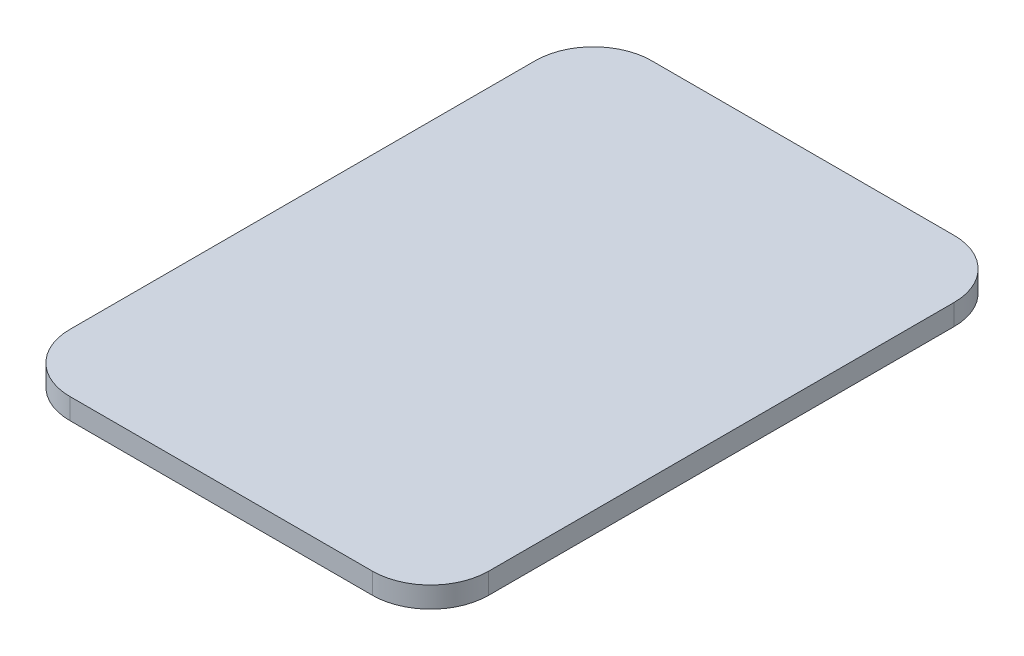
SolidWorks part; units mm, degrees
ref_plane "Front Plane" through (0, 0, 0) normal (0, 0, 1) x (1, 0, 0)
ref_plane "Top Plane" through (0, 0, 0) normal (0, 1, 0) x (1, 0, 0)
ref_plane "Right Plane" through (0, 0, 0) normal (1, 0, 0) x (0, 0, -1)
sketch "Sketch1" plane through (0, 0, 0) normal (0, 1, 0) x (1, 0, 0)
  line L1 (-65, -125) -> (65, -125)
  line L2 (-90, -100) -> (-90, 100)
  line L3 (-65, 125) -> (65, 125)
  line L4 (90, -100) -> (90, 100)
  arc A0 (-90, 100) -> (-65, 125) centre (-65, 100) cw
  arc A1 (65, 125) -> (90, 100) centre (65, 100) cw
  arc A2 (90, -100) -> (65, -125) centre (65, -100) cw
  arc A3 (-65, -125) -> (-90, -100) centre (-65, -100) cw
  point P0 (0, 0)
  point P4 (-90, 0)
  point P6 (0, 125)
  point P19 (0, 0)
  point P20 (0, 0)
  point P21 (0, 0)
  point P22 (0, 0)
  point P23 (0, 0)
  dimension "D3" = 25
  dimension "D1" = 180
  dimension "D2" = 250
extrude "Boss-Extrude1" add sketch "Sketch1" along normal blind 9
